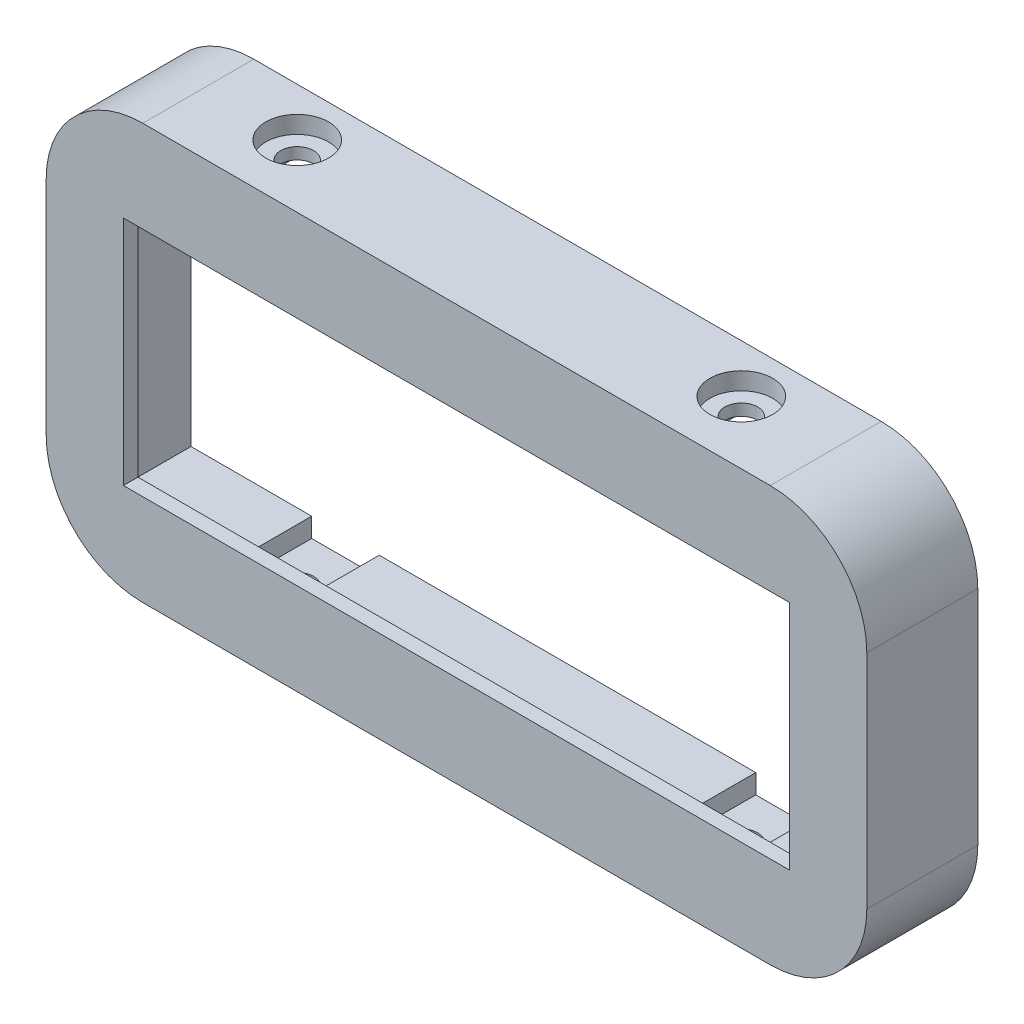
SolidWorks part; units mm, degrees
ref_plane "Přední rovina" through (0, 0, 0) normal (0, 0, 1) x (1, 0, 0)
ref_plane "Horní rovina" through (0, 0, 0) normal (0, 1, 0) x (1, 0, 0)
ref_plane "Pravá rovina" through (0, 0, 0) normal (1, 0, 0) x (0, 0, -1)
sketch "Skica1" plane through (0, 0, 0) normal (0, 0, 1) x (1, 0, 0)
  line L1 (-32.5, 21.5) -> (32.5, 21.5)
  line L2 (-42.5, 11.5) -> (-42.5, -11.5)
  line L3 (-32.5, -21.5) -> (32.5, -21.5)
  line L4 (42.5, 11.5) -> (42.5, -11.5)
  line L5 (-42.5, 21.5) -> (42.5, -21.5) construction
  line L6 (-42.5, -21.5) -> (42.5, 21.5) construction
  line L7 (-34.5, 12) -> (34.5, 12)
  line L8 (-34.5, 12) -> (-34.5, -12)
  line L9 (-34.5, -12) -> (34.5, -12)
  line L10 (34.5, 12) -> (34.5, -12)
  line L11 (-34.5, 12) -> (34.5, -12) construction
  line L12 (-34.5, -12) -> (34.5, 12) construction
  arc A0 (32.5, -21.5) -> (42.5, -11.5) centre (32.5, -11.5) ccw
  arc A1 (32.5, 21.5) -> (42.5, 11.5) centre (32.5, 11.5) cw
  arc A2 (-32.5, 21.5) -> (-42.5, 11.5) centre (-32.5, 11.5) ccw
  arc A3 (-42.5, -11.5) -> (-32.5, -21.5) centre (-32.5, -11.5) ccw
  point P0 (0, 0)
  point P6 (0, 0)
  dimension "D5" = 10
  dimension "D1" = 85
  dimension "D2" = 43
  dimension "D3" = 69
  dimension "D4" = 24
extrude "Přidat vysunutím1" add sketch "Skica1" along normal blind 11.5
sketch "Skica2" plane through (0, 0, 0) normal (0, 0, -1) x (-1, 0, 0)
  line L1 (-39, 16.5) -> (39, 16.5)
  line L2 (-39, 16.5) -> (-39, -16.5)
  line L3 (-39, -16.5) -> (39, -16.5)
  line L4 (39, 16.5) -> (39, -16.5)
  line L5 (-39, 16.5) -> (39, -16.5) construction
  line L6 (-39, -16.5) -> (39, 16.5) construction
  point P0 (0, 0)
  dimension "D1" = 78
  dimension "D2" = 33
extrude "Odebrat vysunutím1" cut sketch "Skica2" against normal blind 10
sketch "Skica3" plane through (0, 0, 0) normal (0, 0, -1) x (-1, 0, 0)
  line L0 (0, 0) -> (0, 16.5)
  line L1 (39, 16.5) -> (-39, 16.5) construction
  line L2 (19.5, 16.5) -> (19.5, 18.5)
  line L3 (-19.5, 16.5) -> (-26.5, 16.5)
  line L4 (-19.5, 16.5) -> (-19.5, 18.5)
  line L5 (-19.5, 18.5) -> (-26.5, 18.5)
  line L6 (-26.5, 16.5) -> (-26.5, 18.5)
  line L7 (19.5, 16.5) -> (26.5, 16.5)
  line L8 (26.5, 16.5) -> (26.5, 18.5)
  line L9 (19.5, 18.5) -> (26.5, 18.5)
  line L10 (0, 0) -> (-17.6807, 0)
  line L11 (-26.5, -16.5) -> (-26.5, -18.5)
  line L12 (19.5, -16.5) -> (26.5, -16.5)
  line L13 (26.5, -16.5) -> (26.5, -18.5)
  line L14 (19.5, -18.5) -> (26.5, -18.5)
  line L15 (19.5, -16.5) -> (19.5, -18.5)
  line L16 (-19.5, -16.5) -> (-19.5, -18.5)
  line L17 (-19.5, -16.5) -> (-26.5, -16.5)
  line L18 (-19.5, -18.5) -> (-26.5, -18.5)
  point P13 (-26.5, 17.5)
  point P23 (-26.5, -17.5)
  line M11 (-39, 16.5) -> (39, 16.5)
  line M13 (39, -16.5) -> (-39, -16.5)
  dimension "D1" = 2
  dimension "D2" = 7
  dimension "D3" = 19.5
extrude "Odebrat vysunutím2" cut sketch "Skica3" against normal blind 10 contours L6 L4 L5 M11 | L9 L2 L8 M11 | L15 L14 L13 M13 | L18 L16 L11 M13
sketch "Skica4" plane through (0, 21.5, 0) normal (0, 1, 0) x (1, 0, 0)
  line L0 (0, 0) -> (0, -11.5)
  line L1 (32.5, 0) -> (-32.5, 0) construction
  line L2 (32.5, -11.5) -> (-32.5, -11.5) construction
  line L3 (0, -5) -> (23, -5)
  point P8 (-23, -5)
  point P9 (23, -5)
  dimension "D1" = 23
  dimension "D2" = 5
hole_wizard "Válcové zahloubení pro M3 šrouby s vnitřním šestihranem2" positions "Skica5" profile "Skica6" counterbore size "M3" standard "DIN"
sketch "Skica5" plane through (0, 21.5, 0) normal (0, 1, 0) x (1, 0, 0)
  point P0 (23, -5)
  point P3 (-23, -5)
sketch "Skica6" plane through (23, 21.5, 5) normal (1, 0, 0) x (0, 0, 1)
  line L0 (0, 0) -> (0, 43)
  line L1 (0, 43) -> (1.7, 43)
  line L3 (1.7, 43) -> (1.7, 1.8)
  line L4 (1.7, 1.8) -> (3.25, 1.8)
  line L5 (3.25, 1.8) -> (3.25, 0)
  line L7 (3.25, 0) -> (0, 0)
  line L11 (0, -6.35) -> (0, 107.95) construction
  dimension "Průměr díry skrz" = 3.4
  dimension "Hloubka díry skrz" = 43
  dimension "Průměr válcového zahloubení" = 6.5
  dimension "Hloubka válcového zahloubení" = 1.8
ref_plane "Rovina1" through (0, 0, 0) normal (0, -1, 0) x (-1, 0, 0)
mirror "Zrcadlit1" about plane through (0, 0, 0) normal (0, -1, 0) of "Válcové zahloubení pro M3 šrouby s vnitřním šestihranem2"
